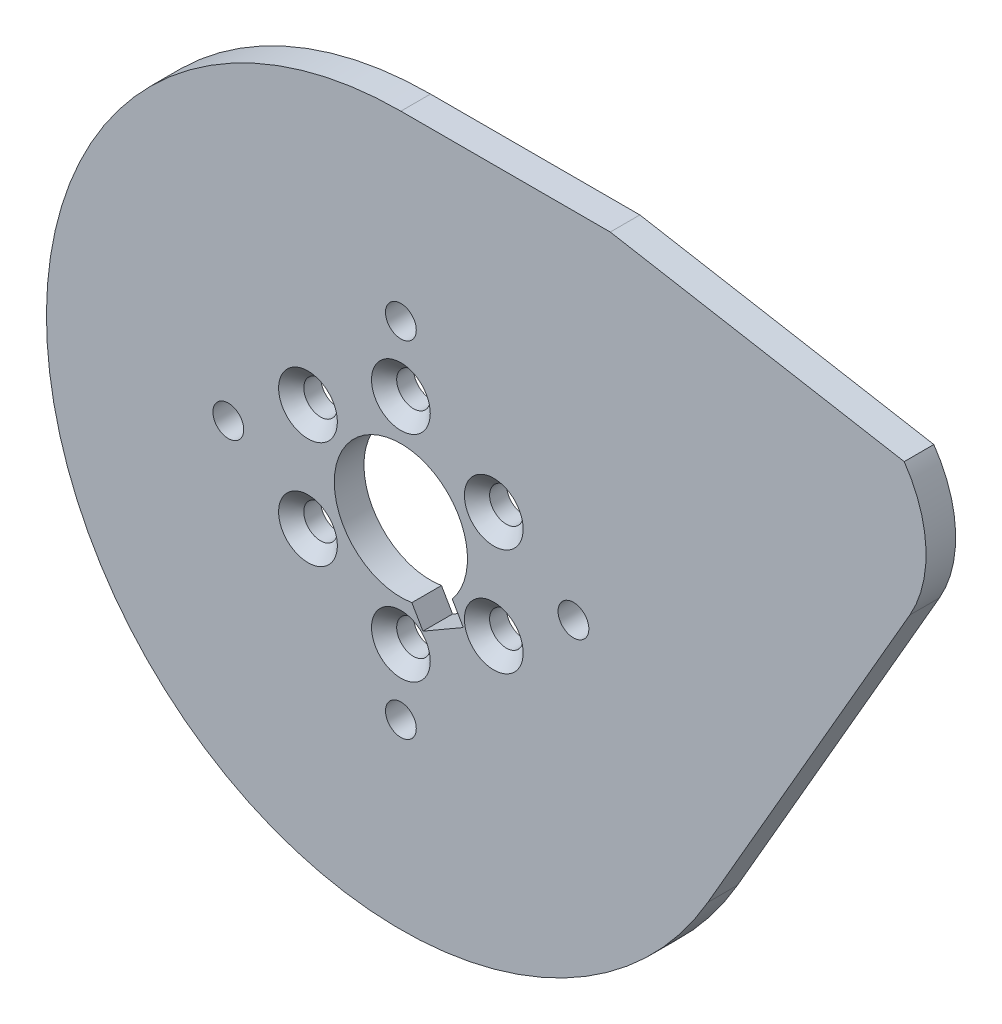
SolidWorks part; units mm, degrees
material "6061 Alloy"
ref_plane "Front" through (0, 0, 0) normal (0, 0, 1) x (1, 0, 0)
ref_plane "Top" through (0, 0, 0) normal (0, 1, 0) x (1, 0, 0)
ref_plane "Right" through (0, 0, 0) normal (1, 0, 0) x (0, 0, -1)
ref_plane "Plane1" through (0, 0, 3.175) normal (0, 0, 1) x (1, 0, 0)
sketch "Sketch1" plane through (0, 0, 3.175) normal (0, 0, 1) x (1, 0, 0)
  line L0 (53.9595, 32.4433) -> (22.4457, 38)
  line L1 (22.4457, 38) -> (0, 38)
  line L2 (32.909, -19) -> (54.5596, 18.5)
  arc A0 (0, 38) -> (32.909, -19) centre (0, 0) ccw
  arc A1 (54.5596, 18.5) -> (53.9595, 32.4433) centre (43.3013, 25) ccw
extrude "Boss-Extrude1" add sketch "Sketch1" against normal blind 3.175
sketch "Sketch2" plane through (0, 0, 0) normal (0, 0, -1) x (-1, 0, 0)
  line L0 (-6.6943, -6.5949) -> (-2.3642, -9.0949)
  line L1 (-2.3642, -9.0949) -> (-1.1776, -7.0396)
  line L2 (-5.5077, -4.5396) -> (-6.6943, -6.5949)
  arc A0 (-1.1776, -7.0396) -> (-5.5077, -4.5396) centre (0, 0) cw
extrude "Cut-Extrude1" cut sketch "Sketch2" against normal through all
ref_plane "Plane2" through (0, 0, 0) normal (0, -1, 0) x (1, 0, 0)
sketch "Sketch3" plane through (0, 0, 0) normal (0, -1, 0) x (1, 0, 0)
  line L0 (7.1374, 3.175) -> (0, 3.175)
  line L1 (0, 3.175) -> (0, 0)
  line L2 (0, 0) -> (7.1374, 0)
  line L3 (7.1374, 0) -> (7.1374, 3.175)
  line L4 (0, 3.175) -> (0, 0) construction
revolve "Cut-Revolve1" cut sketch "Sketch3" angle 360 about L4
hole_wizard "M4x0.7 Tapped Hole1" positions "Sketch5" profile "Sketch4" tap size "M4x0.7" standard "ANSI Metric" end condition through all
sketch "Sketch5" plane through (0, 0, 3.175) normal (0, 0, 1) x (1, 0, 0)
  point P0 (18.5, 0)
  point P1 (0, -18.5)
  point P2 (-18.5, 0)
  point P3 (0, 18.5)
sketch "Sketch4" plane through (18.5, 0, 3.175) normal (1, 0, 0) x (0, -1, 0)
  line L0 (0, 0) -> (0, 3.175)
  line L1 (0, 3.175) -> (1.65, 3.175)
  line L2 (1.65, 3.175) -> (1.65, 0)
  line L5 (1.65, 0) -> (0, 0)
  line L11 (0, -6.35) -> (0, 107.95) construction
  dimension "Thru Tap Drill Dia." = 3.3
  dimension "Thru Tap Drill Depth" = 3.175
hole_wizard "CSK for M3 Flat Head Machine Screw1" positions "Sketch7" profile "Sketch6" countersink size "M3" standard "ANSI Metric" end condition through all
sketch "Sketch7" plane through (0, 0, 3.175) normal (0, 0, 1) x (1, 0, 0)
  point P0 (-9.9593, 5.75)
  point P1 (-9.9593, -5.75)
  point P2 (0, -11.5)
  point P3 (9.9593, -5.75)
  point P4 (9.9593, 5.75)
  point P5 (0, 11.5)
sketch "Sketch6" plane through (-9.9593, 5.75, 3.175) normal (1, 0, 0) x (0, -1, 0)
  line L0 (0, 0) -> (0, 3.175)
  line L1 (0, 3.175) -> (1.8, 3.175)
  line L2 (1.8, 3.175) -> (1.8, 1.35)
  line L3 (1.8, 1.35) -> (3.15, 0)
  line L5 (3.15, 0) -> (0, 0)
  line L6 (-1.8, 1.35) -> (-3.15, 0) construction
  line L11 (0, -6.35) -> (0, 107.95) construction
  dimension "Thru Hole Dia." = 3.6
  dimension "Thru Hole Depth" = 3.175
  dimension "Near C'Sink Dia." = 6.3
  dimension "Near C'Sink Angle" = 90
